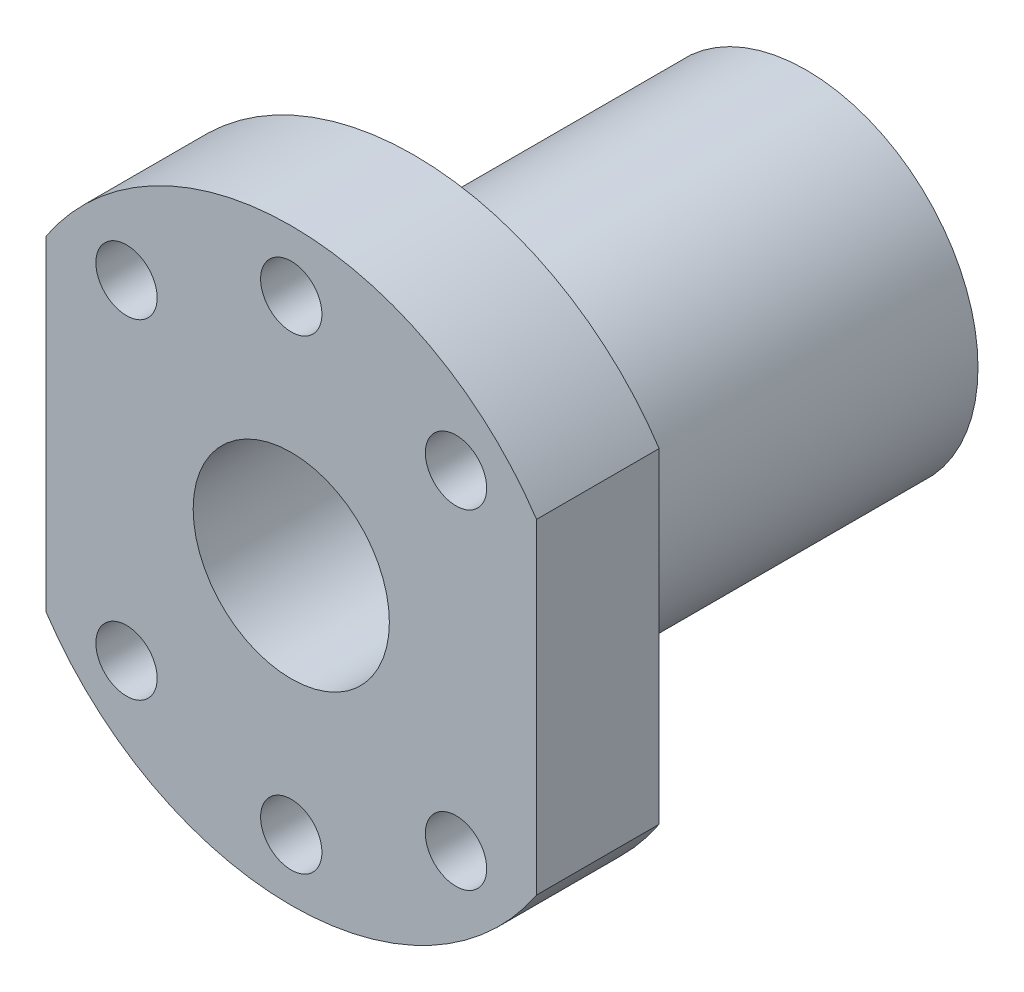
SolidWorks part; units mm, degrees
ref_plane "Front Plane" through (0, 0, 0) normal (0, 0, 1) x (1, 0, 0)
ref_plane "Top Plane" through (0, 0, 0) normal (0, 1, 0) x (1, 0, 0)
ref_plane "Right Plane" through (0, 0, 0) normal (1, 0, 0) x (0, 0, -1)
sketch "Sketch1" plane through (0, 0, 0) normal (0, 0, 1) x (1, 0, 0)
  line L2 (-20, 13.2665) -> (-20, -13.2665)
  line L4 (20, 13.2665) -> (20, -13.2665)
  arc A0 (-20, -13.2665) -> (20, -13.2665) centre (0, 0) ccw
  arc A1 (20, 13.2665) -> (-20, 13.2665) centre (0, 0) ccw
  dimension "D1" = 48
  dimension "D2" = 40
  dimension "D3" = 20
extrude "Boss-Extrude1" add sketch "Sketch1" along normal blind 10
sketch "Sketch2" plane through (0, 0, 0) normal (0, 0, -1) x (-1, 0, 0)
  circle A0 centre (0, 0) radius 14
  dimension "D1" = 28
extrude "Boss-Extrude2" add sketch "Sketch2" along normal blind 32
sketch "Sketch3" plane through (0, 0, -32) normal (0, 0, -1) x (-1, 0, 0)
  circle A0 centre (0, 0) radius 8
  dimension "D1" = 16
extrude "Cut-Extrude1" cut sketch "Sketch3" against normal through all
hole_wizard "Ø5.0mm Dowel Hole1" positions "Sketch5" profile "Sketch4" hole size "Ø5.0" standard "ISO" end condition through all
sketch "Sketch5" plane through (0, 0, 10) normal (0, 0, 1) x (1, 0, 0)
  point P0 (0, 19)
  dimension "D1" = 19
sketch "Sketch4" plane through (0, 19, 10) normal (1, 0, 0) x (0, -1, 0)
  line L0 (0, 0) -> (0, 42)
  line L1 (0, 42) -> (2.5, 42)
  line L2 (2.5, 42) -> (2.5, 0)
  line L5 (2.5, 0) -> (0, 0)
  line L11 (0, -6.35) -> (0, 107.95) construction
  dimension "Thru Hole Dia." = 5
  dimension "Thru Hole Depth" = 42
pattern_circular "CirPattern1" count 8 every 45 about axis through (0, 0, 0) along (0, 0, 1) of "Ø5.0mm Dowel Hole1"
